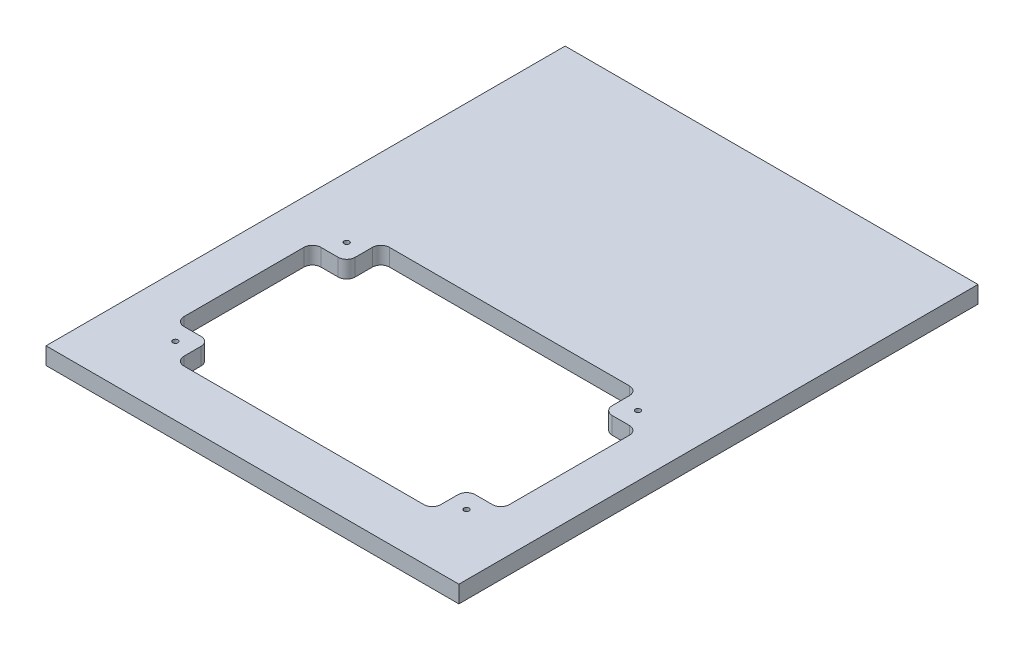
SolidWorks part; units mm, degrees
ref_plane "Front Plane" through (0, 0, 0) normal (0, 0, 1) x (1, 0, 0)
ref_plane "Top Plane" through (0, 0, 0) normal (0, 1, 0) x (1, 0, 0)
ref_plane "Right Plane" through (0, 0, 0) normal (1, 0, 0) x (0, 0, -1)
sketch "Sketch1" plane through (0, 0, 0) normal (0, 1, 0) x (1, 0, 0)
  line L1 (0, 0) -> (241, 0)
  line L2 (0, 0) -> (0, 303)
  line L3 (0, 303) -> (241, 303)
  line L4 (241, 0) -> (241, 303)
  dimension "D1" = 241
  dimension "D2" = 303
extrude "Boss-Extrude1" add sketch "Sketch1" along normal blind 10
sketch "Sketch2" plane through (0, 10, 0) normal (0, 1, 0) x (1, 0, 0)
  line L0 (0, 0) -> (241, 0) construction
  line L1 (50.5, 150) -> (190.5, 150)
  line L2 (45.5, 145) -> (45.5, 135)
  line L3 (50.5, 30) -> (190.5, 30)
  line L4 (195.5, 145) -> (195.5, 135)
  line L5 (0, 151.5) -> (25.5, 151.5) construction
  line L6 (0, 303) -> (0, 0) construction
  line L7 (120.5, 303) -> (120.5, 150) construction
  line L8 (241, 0) -> (241, 303) construction
  line L9 (215.5, 151.5) -> (241, 151.5) construction
  line L10 (30.5, 50) -> (40.5, 50)
  line L11 (25.5, 55) -> (25.5, 125)
  line L12 (30.5, 130) -> (40.5, 130)
  line L14 (195.5, 45) -> (195.5, 35)
  line L15 (120.5, 30) -> (120.5, 0) construction
  line L16 (210.5, 50) -> (200.5, 50)
  line L17 (215.5, 55) -> (215.5, 125)
  line L18 (210.5, 130) -> (200.5, 130)
  line L22 (45.5, 45) -> (45.5, 35)
  arc A0 (50.5, 150) -> (45.5, 145) centre (50.5, 145) ccw
  arc A1 (190.5, 150) -> (195.5, 145) centre (190.5, 145) cw
  arc A2 (200.5, 130) -> (195.5, 135) centre (200.5, 135) cw
  arc A3 (215.5, 125) -> (210.5, 130) centre (210.5, 125) ccw
  arc A4 (210.5, 50) -> (215.5, 55) centre (210.5, 55) ccw
  arc A5 (200.5, 50) -> (195.5, 45) centre (200.5, 45) ccw
  arc A6 (190.5, 30) -> (195.5, 35) centre (190.5, 35) ccw
  arc A7 (40.5, 50) -> (45.5, 45) centre (40.5, 45) cw
  arc A8 (50.5, 30) -> (45.5, 35) centre (50.5, 35) cw
  arc A9 (30.5, 50) -> (25.5, 55) centre (30.5, 55) cw
  arc A10 (25.5, 125) -> (30.5, 130) centre (30.5, 125) cw
  arc A11 (40.5, 130) -> (45.5, 135) centre (40.5, 135) ccw
  point P9 (120.5, 0)
  point P15 (120.5, 30)
  point P17 (77.9806, 74.476)
  point P22 (257.9806, 74.476)
  point P29 (45.5, 150)
  point P35 (195.5, 150)
  point P38 (195.5, 130)
  point P41 (215.5, 130)
  point P44 (215.5, 50)
  point P47 (195.5, 50)
  point P50 (195.5, 30)
  point P53 (45.5, 50)
  point P56 (45.5, 30)
  point P59 (25.5, 50)
  point P62 (25.5, 130)
  point P65 (45.5, 130)
  dimension "D9" = 5
  dimension "D1" = 120
  dimension "D2" = 150
  dimension "D3" = 20
  dimension "D4" = 20
  dimension "D5" = 80
  dimension "D6" = 20
  dimension "D7" = 20
  dimension "D8" = 80
  dimension "D10" = 30
extrude "Cut-Extrude1" cut sketch "Sketch2" against normal through all
sketch "Sketch3" plane through (0, 10, 0) normal (0, 1, 0) x (1, 0, 0)
  line L0 (45.5, 145) -> (45.5, 135) construction
  line L1 (40.5, 130) -> (30.5, 130) construction
  line L2 (30.5, 50) -> (40.5, 50) construction
  line L4 (195.5, 135) -> (195.5, 145) construction
  line L5 (210.5, 130) -> (200.5, 130) construction
  line L6 (200.5, 50) -> (210.5, 50) construction
  circle A0 centre (205.5, 140) radius 1.5
  circle A1 centre (35.5, 140) radius 1.5
  circle A2 centre (35.5, 40) radius 1.5
  circle A3 centre (205.5, 40) radius 1.5
  dimension "D1" = 3
  dimension "D2" = 3
  dimension "D3" = 3
  dimension "D4" = 3
  dimension "D5" = 10
  dimension "D6" = 10
  dimension "D7" = 10
  dimension "D8" = 10
  dimension "D9" = 10
  dimension "D10" = 10
extrude "Cut-Extrude2" cut sketch "Sketch3" against normal blind 10
